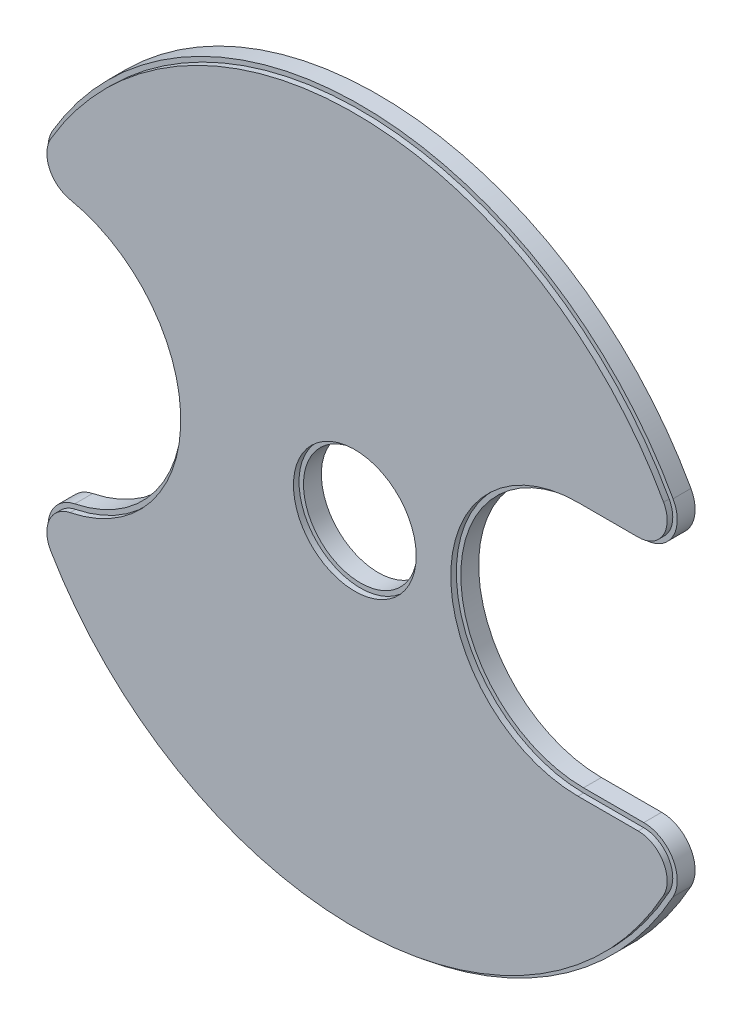
SolidWorks part; units mm, degrees
ref_plane "Plan de face" through (0, 0, 0) normal (0, 0, 1) x (1, 0, 0)
ref_plane "Plan de dessus" through (0, 0, 0) normal (0, 1, 0) x (1, 0, 0)
ref_plane "Plan de droite" through (0, 0, 0) normal (1, 0, 0) x (0, 0, -1)
sketch "Esquisse1" plane through (0, 0, 0) normal (0, 0, 1) x (1, 0, 0)
  line L0 (30.05, 11) -> (20, 11)
  line L1 (0, 0) -> (23.2256, 0) construction
  line L2 (30.05, -11) -> (20, -11)
  circle A0 centre (0, 0) radius 5.1
  arc A1 (20, 11) -> (20, -11) centre (20, 0) ccw
  arc A2 (30.05, 11) -> (30.05, -11) centre (0, 0) ccw construction
  arc A3 (-29.7143, 11.8769) -> (-29.7143, -11.8769) centre (-28, 0) cw
  arc A4 (-29.7143, 11.8769) -> (30.05, 11) centre (0, 0) cw
  arc A5 (-29.7143, -11.8769) -> (30.05, -11) centre (0, 0) ccw
  dimension "D1" = 10.2
  dimension "D3" = 32
  dimension "D5" = 28
  dimension "D6" = 12
  dimension "D2" = 22
  dimension "D4" = 20
extrude "Boss.-Extru.1" add sketch "Esquisse1" along normal blind 1.6
fillet "Congé1" radius 3 4 edges at (-29.7143, -11.8769, 0.8) (-29.7143, 11.8769, 0.8) (30.05, -11, 0.8) (30.05, 11, 0.8)
sketch "Esquisse2" plane through (0, 0, 1.6) normal (0, 0, 1) x (1, 0, 0)
  line L12 (20, 11.4) -> (25.3969, 11.4)
  line L13 (25.3969, -11.4) -> (20, -11.4)
  line L14 (20, 11.4) -> (25.3969, 11.4)
  line L15 (25.3969, -11.4) -> (20, -11.4)
  circle A6 centre (0, 0) radius 5.5
  circle A7 centre (0, 0) radius 5.5
  arc A28 (25.3969, 11.4) -> (27.6738, 15.2552) centre (25.3969, 14) ccw
  arc A29 (27.6738, 15.2552) -> (-27.2414, 16.0146) centre (0, 0) ccw
  arc A30 (-27.2414, 16.0146) -> (-25.52, 12.1495) centre (-25, 14.6969) ccw
  arc A31 (-25.52, -12.1495) -> (-25.52, 12.1495) centre (-28, 0) ccw
  arc A32 (-25.52, -12.1495) -> (-27.2414, -16.0146) centre (-25, -14.6969) ccw
  arc A33 (-27.2414, -16.0146) -> (27.6738, -15.2552) centre (0, 0) ccw
  arc A34 (27.6738, -15.2552) -> (25.3969, -11.4) centre (25.3969, -14) ccw
  arc A35 (20, 11.4) -> (20, -11.4) centre (20, 0) ccw
  arc A36 (25.3969, 11.4) -> (27.6738, 15.2552) centre (25.3969, 14) ccw
  arc A37 (27.6738, 15.2552) -> (-27.2414, 16.0146) centre (0, 0) ccw
  arc A38 (-27.2414, 16.0146) -> (-25.52, 12.1495) centre (-25, 14.6969) ccw
  arc A39 (-25.52, -12.1495) -> (-25.52, 12.1495) centre (-28, 0) ccw
  arc A40 (-25.52, -12.1495) -> (-27.2414, -16.0146) centre (-25, -14.6969) ccw
  arc A41 (-27.2414, -16.0146) -> (27.6738, -15.2552) centre (0, 0) ccw
  arc A42 (27.6738, -15.2552) -> (25.3969, -11.4) centre (25.3969, -14) ccw
  arc A43 (20, 11.4) -> (20, -11.4) centre (20, 0) ccw
  dimension "D1" = 0.4
  dimension "D2" = 0.4
extrude "Boss.-Extru.2" add sketch "Esquisse2" along normal blind 0.5
